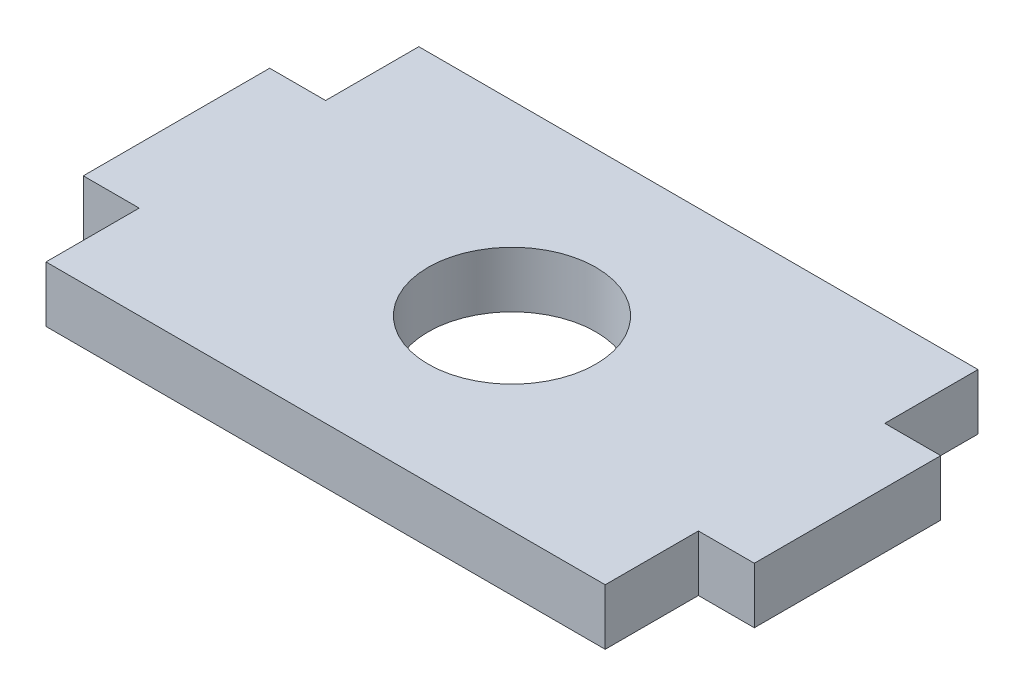
SolidWorks part; units mm, degrees
ref_plane "Alzado" through (0, 0, 0) normal (0, 0, 1) x (1, 0, 0)
ref_plane "Planta" through (0, 0, 0) normal (0, 1, 0) x (1, 0, 0)
ref_plane "Vista lateral" through (0, 0, 0) normal (1, 0, 0) x (0, 0, -1)
sketch "Croquis1" plane through (0, 0, 0) normal (0, 1, 0) x (1, 0, 0)
  line L0 (0, -5) -> (0, 5)
  line L1 (0, 5) -> (3, 5)
  line L2 (3, 5) -> (3, 10)
  line L3 (3, 10) -> (33, 10)
  line L5 (33, 5) -> (33, 10)
  line L6 (36, 5) -> (33, 5)
  line L7 (36, -5) -> (36, 5)
  line L9 (36, -5) -> (33, -5)
  line L10 (33, -5) -> (33, -10)
  line L12 (3, -10) -> (33, -10)
  line L13 (3, -5) -> (3, -10)
  line L14 (0, -5) -> (3, -5)
  circle A0 centre (18, 0) radius 4.5
  point P13 (36, 0)
  dimension "D1" = 9
  dimension "D2" = 3
  dimension "D3" = 5
  dimension "D4" = 30
extrude "Saliente-Extruir1" add sketch "Croquis1" along normal blind 3
